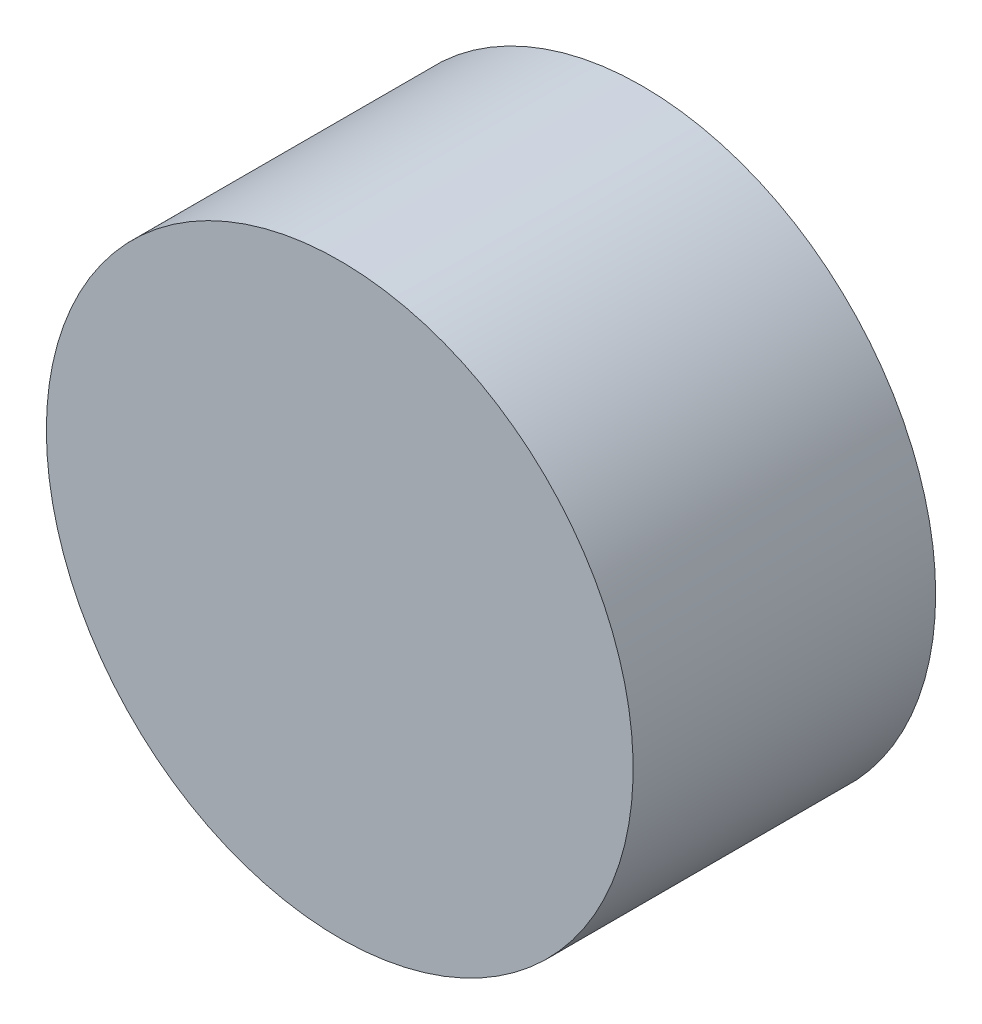
SolidWorks part; units mm, degrees
ref_plane "Front Plane" through (0, 0, 0) normal (0, 0, 1) x (1, 0, 0)
ref_plane "Top Plane" through (0, 0, 0) normal (0, 1, 0) x (1, 0, 0)
ref_plane "Right Plane" through (0, 0, 0) normal (1, 0, 0) x (0, 0, -1)
sketch "Sketch1" plane through (0, 0, 0) normal (0, 0, 1) x (1, 0, 0)
  line L0 (-64.4613, 54.2738) -> (-64.4613, -54.2738)
  line L1 (-62.4613, 52.2738) -> (62.4613, 52.2738)
  line L2 (-62.4613, 52.2738) -> (-62.4613, -52.2738)
  line L3 (-62.4613, -52.2738) -> (62.4613, -52.2738)
  line L4 (62.4613, 52.2738) -> (62.4613, -52.2738)
  line L5 (-62.4613, 52.2738) -> (62.4613, -52.2738) construction
  line L6 (-62.4613, -52.2738) -> (62.4613, 52.2738) construction
  line L7 (-64.4613, -54.2738) -> (64.4613, -54.2738)
  line L8 (64.4613, 54.2738) -> (64.4613, -54.2738)
  line L9 (-64.4613, 54.2738) -> (64.4613, 54.2738)
  point P0 (0, 0)
  dimension "D1" = 2
extrude "Boss-Extrude1" add sketch "Sketch1" along normal blind 50
sketch "Sketch2" plane through (0, 0, 0) normal (0, 0, 1) x (1, 0, 0)
  circle A0 centre (0, 0) radius 48.4966
extrude "Boss-Extrude2" add sketch "Sketch2" along normal up to surface (50 mm away) separate body up to face at (0, 0, 50)
sketch "Sketch3" plane through (0, 0, 0) normal (0, 0, 1) x (1, 0, 0)
  circle A0 centre (-51.1264, 41.5168) radius 6.9941
  circle A1 centre (46.4615, 43.756) radius 6.1207
extrude "Boss-Extrude3" add sketch "Sketch3" along normal blind 20 separate body
delete or keep bodies "Body-Delete1" type delete bodies bodies 104 103 101
